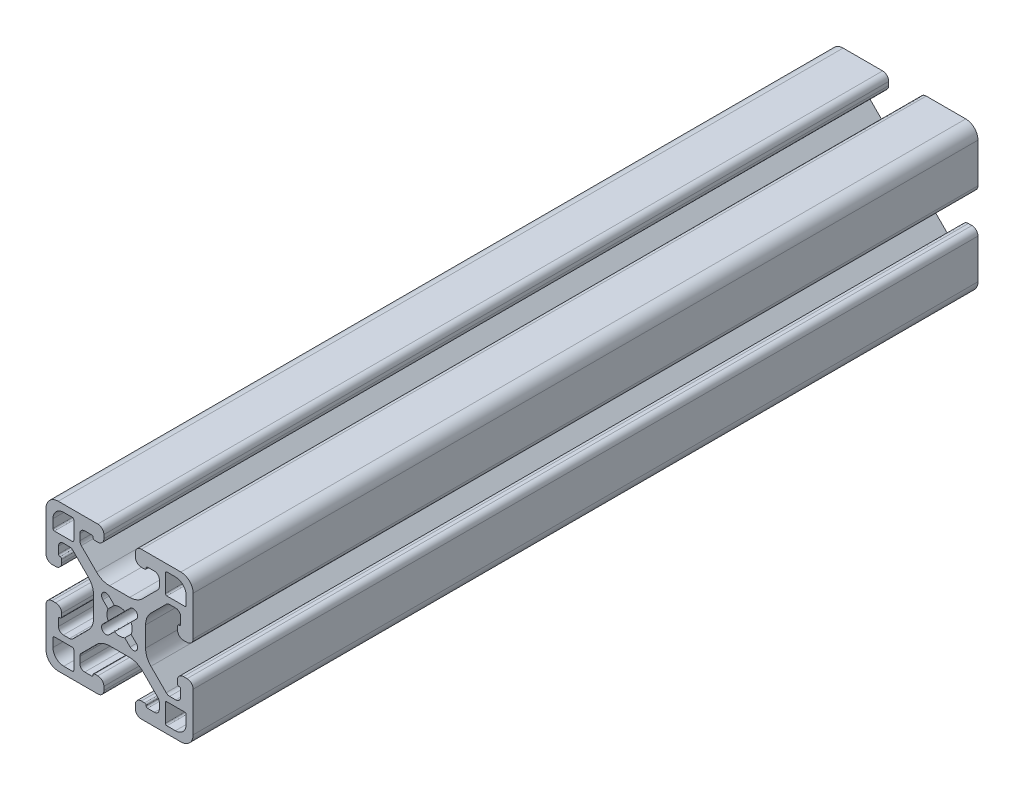
SolidWorks part; units mm, degrees
ref_plane "Front Plane" through (0, 0, 0) normal (0, 0, 1) x (1, 0, 0)
ref_plane "Top Plane" through (0, 0, 0) normal (0, 1, 0) x (1, 0, 0)
ref_plane "Right Plane" through (0, 0, 0) normal (1, 0, 0) x (0, 0, -1)
sketch "Sketch1" plane through (0, 0, 0) normal (0, 0, 1) x (1, 0, 0)
  line L0 (-66.7042, -2.4885) -> (-65.3338, -1.1181)
  line L1 (-65.3338, 1.5948) -> (-66.7042, 2.9652)
  line L2 (-65.0878, 4.5817) -> (-63.7174, 3.2113)
  line L3 (-61.0045, 3.2113) -> (-59.7212, 4.484)
  line L4 (-58.1153, 2.8781) -> (-59.3881, 1.5948)
  line L5 (-59.3881, -1.1181) -> (-58.0176, -2.4885)
  line L6 (-59.6341, -4.1049) -> (-61.0045, -2.7345)
  line L7 (-63.7174, -2.7345) -> (-65.0878, -4.1049)
  line L8 (-79.6075, 12.4812) -> (-79.6075, 14.691)
  line L9 (-76.8135, 17.485) -> (-74.6037, 17.485)
  line L10 (-74.2227, 17.104) -> (-74.2227, 12.4812)
  line L11 (-74.6037, 12.1002) -> (-79.2265, 12.1002)
  line L12 (-74.6037, -17.0082) -> (-76.8135, -17.0082)
  line L13 (-79.6075, -14.2142) -> (-79.6075, -12.0044)
  line L14 (-79.2265, -11.6234) -> (-74.6037, -11.6234)
  line L15 (-74.2227, -12.0044) -> (-74.2227, -16.6272)
  line L16 (-45.1143, -12.0044) -> (-45.1143, -14.2142)
  line L17 (-47.9083, -17.0082) -> (-50.1181, -17.0082)
  line L18 (-50.4991, -16.6272) -> (-50.4991, -12.0044)
  line L19 (-50.1181, -11.6234) -> (-45.4953, -11.6234)
  line L20 (-50.1181, 17.485) -> (-47.9083, 17.485)
  line L21 (-45.1143, 14.691) -> (-45.1143, 12.4812)
  line L22 (-45.4953, 12.1002) -> (-50.1181, 12.1002)
  line L23 (-50.4991, 12.4812) -> (-50.4991, 17.104)
  line L24 (-46.5368, -7.0006) -> (-46.5368, -8.7746)
  line L25 (-47.8067, -10.0486) -> (-49.3926, -10.0486)
  line L26 (-50.2907, -9.6767) -> (-54.2388, -5.7286)
  line L27 (-55.6299, -2.3699) -> (-55.6299, 2.8467)
  line L28 (-54.2388, 6.2053) -> (-50.2907, 10.1534)
  line L29 (-49.3926, 10.5254) -> (-47.8067, 10.5254)
  line L30 (-46.5368, 9.2513) -> (-46.5368, 7.4774)
  line L31 (-46.9178, 7.0964) -> (-46.994, 7.0964)
  line L32 (-47.375, 6.7154) -> (-47.3749, 5.8772)
  line L33 (-45.8001, 4.3024) -> (-44.8857, 4.3024)
  line L34 (-43.3109, 5.8772) -> (-43.3109, 16.1134)
  line L35 (-46.4859, 19.2884) -> (-56.7221, 19.2884)
  line L36 (-58.2969, 17.7136) -> (-58.2969, 16.7992)
  line L37 (-56.7222, 15.2244) -> (-55.884, 15.2244)
  line L38 (-55.503, 15.6054) -> (-55.503, 15.6816)
  line L39 (-55.122, 16.0626) -> (-53.348, 16.0626)
  line L40 (-52.0739, 14.7926) -> (-52.0739, 13.2067)
  line L41 (-52.4459, 12.3087) -> (-56.394, 8.3606)
  line L42 (-59.7526, 6.9694) -> (-64.9693, 6.9694)
  line L43 (-68.3279, 8.3606) -> (-72.276, 12.3087)
  line L44 (-72.6479, 13.2067) -> (-72.6479, 14.7926)
  line L45 (-71.3739, 16.0626) -> (-69.5999, 16.0626)
  line L46 (-69.2189, 15.6816) -> (-69.2189, 15.6054)
  line L47 (-68.8379, 15.2244) -> (-67.9997, 15.2244)
  line L48 (-66.4249, 16.7992) -> (-66.4249, 17.7136)
  line L49 (-67.9997, 19.2884) -> (-78.2359, 19.2884)
  line L50 (-81.4109, 16.1134) -> (-81.4109, 5.8772)
  line L51 (-79.8361, 4.3024) -> (-78.9217, 4.3024)
  line L52 (-77.3469, 5.8772) -> (-77.3469, 6.7154)
  line L53 (-77.7279, 7.0964) -> (-77.8041, 7.0964)
  line L54 (-78.1851, 7.4774) -> (-78.1851, 9.2513)
  line L55 (-76.9151, 10.5254) -> (-75.3293, 10.5254)
  line L56 (-74.4312, 10.1534) -> (-70.4831, 6.2053)
  line L57 (-69.0919, 2.8467) -> (-69.0919, -2.3699)
  line L58 (-70.4831, -5.7286) -> (-74.4312, -9.6767)
  line L59 (-75.3293, -10.0486) -> (-76.9151, -10.0486)
  line L60 (-78.1851, -8.7746) -> (-78.1851, -7.0006)
  line L61 (-77.8041, -6.6196) -> (-77.7279, -6.6196)
  line L62 (-77.3469, -6.2386) -> (-77.3469, -5.4004)
  line L63 (-78.9217, -3.8256) -> (-79.8361, -3.8256)
  line L64 (-81.4109, -5.4004) -> (-81.4109, -15.6366)
  line L65 (-78.2359, -18.8116) -> (-67.9997, -18.8116)
  line L66 (-66.4249, -17.2368) -> (-66.4249, -16.3224)
  line L67 (-67.9997, -14.7476) -> (-68.8379, -14.7476)
  line L68 (-69.2189, -15.1286) -> (-69.2189, -15.2048)
  line L69 (-69.5999, -15.5858) -> (-71.3739, -15.5858)
  line L70 (-72.6479, -14.3158) -> (-72.6479, -12.7299)
  line L71 (-72.276, -11.8319) -> (-68.3279, -7.8838)
  line L72 (-64.9693, -6.4926) -> (-59.7526, -6.4926)
  line L73 (-56.394, -7.8838) -> (-52.4459, -11.8319)
  line L74 (-52.0739, -12.7299) -> (-52.0739, -14.3158)
  line L75 (-53.348, -15.5858) -> (-55.122, -15.5858)
  line L76 (-55.503, -15.2048) -> (-55.503, -15.1286)
  line L77 (-55.884, -14.7476) -> (-56.7222, -14.7476)
  line L78 (-58.2969, -16.3224) -> (-58.2969, -17.2368)
  line L79 (-56.7221, -18.8116) -> (-46.4859, -18.8116)
  line L80 (-43.3109, -15.6366) -> (-43.3109, -5.4004)
  line L81 (-44.8857, -3.8256) -> (-45.8001, -3.8256)
  line L82 (-47.3749, -5.4004) -> (-47.375, -6.2386)
  line L83 (-46.994, -6.6196) -> (-46.9178, -6.6196)
  arc A0 (-66.7042, -2.4885) -> (-65.0878, -4.1049) centre (-65.896, -3.2967) ccw
  arc A1 (-65.3338, 1.5948) -> (-65.3338, -1.1181) centre (-62.3609, 0.2384) ccw
  arc A2 (-65.0878, 4.5817) -> (-66.7042, 2.9652) centre (-65.896, 3.7734) ccw
  arc A3 (-61.0045, 3.2113) -> (-63.7174, 3.2113) centre (-62.3609, 0.2384) ccw
  arc A4 (-58.1153, 2.8781) -> (-59.7212, 4.484) centre (-58.8259, 3.7734) ccw
  arc A5 (-59.3881, -1.1181) -> (-59.3881, 1.5948) centre (-62.3609, 0.2384) ccw
  arc A6 (-59.6341, -4.1049) -> (-58.0176, -2.4885) centre (-58.8259, -3.2967) ccw
  arc A7 (-63.7174, -2.7345) -> (-61.0045, -2.7345) centre (-62.3609, 0.2384) ccw
  arc A8 (-79.6075, 12.4812) -> (-79.2265, 12.1002) centre (-79.2265, 12.4812) ccw
  arc A9 (-76.8135, 17.485) -> (-79.6075, 14.691) centre (-76.8135, 14.691) ccw
  arc A10 (-74.2227, 17.104) -> (-74.6037, 17.485) centre (-74.6037, 17.104) ccw
  arc A11 (-74.6037, 12.1002) -> (-74.2227, 12.4812) centre (-74.6037, 12.4812) ccw
  arc A12 (-74.6037, -17.0082) -> (-74.2227, -16.6272) centre (-74.6037, -16.6272) ccw
  arc A13 (-79.6075, -14.2142) -> (-76.8135, -17.0082) centre (-76.8135, -14.2142) ccw
  arc A14 (-79.2265, -11.6234) -> (-79.6075, -12.0044) centre (-79.2265, -12.0044) ccw
  arc A15 (-74.2227, -12.0044) -> (-74.6037, -11.6234) centre (-74.6037, -12.0044) ccw
  arc A16 (-45.1143, -12.0044) -> (-45.4953, -11.6234) centre (-45.4953, -12.0044) ccw
  arc A17 (-47.9083, -17.0082) -> (-45.1143, -14.2142) centre (-47.9083, -14.2142) ccw
  arc A18 (-50.4991, -16.6272) -> (-50.1181, -17.0082) centre (-50.1181, -16.6272) ccw
  arc A19 (-50.1181, -11.6234) -> (-50.4991, -12.0044) centre (-50.1181, -12.0044) ccw
  arc A20 (-50.1181, 17.485) -> (-50.4991, 17.104) centre (-50.1181, 17.104) ccw
  arc A21 (-45.1143, 14.691) -> (-47.9083, 17.485) centre (-47.9083, 14.691) ccw
  arc A22 (-45.4953, 12.1002) -> (-45.1143, 12.4812) centre (-45.4953, 12.4812) ccw
  arc A23 (-50.4991, 12.4812) -> (-50.1181, 12.1002) centre (-50.1181, 12.4812) ccw
  arc A24 (-47.8067, -10.0486) -> (-46.5368, -8.7746) centre (-47.8067, -8.7786) ccw
  arc A25 (-50.2907, -9.6767) -> (-49.3926, -10.0486) centre (-49.3926, -8.7786) ccw
  arc A26 (-55.6299, -2.3699) -> (-54.2388, -5.7286) centre (-50.8801, -2.3699) ccw
  arc A27 (-54.2388, 6.2053) -> (-55.6299, 2.8467) centre (-50.8801, 2.8467) ccw
  arc A28 (-49.3926, 10.5254) -> (-50.2907, 10.1534) centre (-49.3926, 9.2554) ccw
  arc A29 (-46.5368, 9.2513) -> (-47.8067, 10.5254) centre (-47.8067, 9.2554) ccw
  arc A30 (-46.9178, 7.0964) -> (-46.5368, 7.4774) centre (-46.9178, 7.4774) ccw
  arc A31 (-46.994, 7.0964) -> (-47.375, 6.7154) centre (-46.994, 6.7154) ccw
  arc A32 (-47.3749, 5.8772) -> (-45.8001, 4.3024) centre (-45.8001, 5.8772) ccw
  arc A33 (-44.8857, 4.3024) -> (-43.3109, 5.8772) centre (-44.8857, 5.8772) ccw
  arc A34 (-43.3109, 16.1134) -> (-46.4859, 19.2884) centre (-46.4859, 16.1134) ccw
  arc A35 (-56.7221, 19.2884) -> (-58.2969, 17.7136) centre (-56.7221, 17.7136) ccw
  arc A36 (-58.2969, 16.7992) -> (-56.7222, 15.2244) centre (-56.7221, 16.7992) ccw
  arc A37 (-55.884, 15.2244) -> (-55.503, 15.6054) centre (-55.884, 15.6054) ccw
  arc A38 (-55.122, 16.0626) -> (-55.503, 15.6816) centre (-55.122, 15.6816) ccw
  arc A39 (-52.0739, 14.7926) -> (-53.348, 16.0626) centre (-53.3439, 14.7926) ccw
  arc A40 (-52.4459, 12.3087) -> (-52.0739, 13.2067) centre (-53.3439, 13.2067) ccw
  arc A41 (-59.7526, 6.9694) -> (-56.394, 8.3606) centre (-59.7526, 11.7192) ccw
  arc A42 (-68.3279, 8.3606) -> (-64.9693, 6.9694) centre (-64.9693, 11.7192) ccw
  arc A43 (-72.6479, 13.2067) -> (-72.276, 12.3087) centre (-71.3779, 13.2067) ccw
  arc A44 (-71.3739, 16.0626) -> (-72.6479, 14.7926) centre (-71.3779, 14.7926) ccw
  arc A45 (-69.2189, 15.6816) -> (-69.5999, 16.0626) centre (-69.5999, 15.6816) ccw
  arc A46 (-69.2189, 15.6054) -> (-68.8379, 15.2244) centre (-68.8379, 15.6054) ccw
  arc A47 (-67.9997, 15.2244) -> (-66.4249, 16.7992) centre (-67.9997, 16.7992) ccw
  arc A48 (-66.4249, 17.7136) -> (-67.9997, 19.2884) centre (-67.9997, 17.7136) ccw
  arc A49 (-78.2359, 19.2884) -> (-81.4109, 16.1134) centre (-78.2359, 16.1134) ccw
  arc A50 (-81.4109, 5.8772) -> (-79.8361, 4.3024) centre (-79.8361, 5.8772) ccw
  arc A51 (-78.9217, 4.3024) -> (-77.3469, 5.8772) centre (-78.9217, 5.8772) ccw
  arc A52 (-77.3469, 6.7154) -> (-77.7279, 7.0964) centre (-77.7279, 6.7154) ccw
  arc A53 (-78.1851, 7.4774) -> (-77.8041, 7.0964) centre (-77.8041, 7.4774) ccw
  arc A54 (-76.9151, 10.5254) -> (-78.1851, 9.2513) centre (-76.9151, 9.2554) ccw
  arc A55 (-74.4312, 10.1534) -> (-75.3293, 10.5254) centre (-75.3293, 9.2554) ccw
  arc A56 (-69.0919, 2.8467) -> (-70.4831, 6.2053) centre (-73.8417, 2.8467) ccw
  arc A57 (-70.4831, -5.7286) -> (-69.0919, -2.3699) centre (-73.8417, -2.3699) ccw
  arc A58 (-75.3293, -10.0486) -> (-74.4312, -9.6767) centre (-75.3293, -8.7786) ccw
  arc A59 (-78.1851, -8.7746) -> (-76.9151, -10.0486) centre (-76.9151, -8.7786) ccw
  arc A60 (-77.8041, -6.6196) -> (-78.1851, -7.0006) centre (-77.8041, -7.0006) ccw
  arc A61 (-77.7279, -6.6196) -> (-77.3469, -6.2386) centre (-77.7279, -6.2386) ccw
  arc A62 (-77.3469, -5.4004) -> (-78.9217, -3.8256) centre (-78.9217, -5.4004) ccw
  arc A63 (-79.8361, -3.8256) -> (-81.4109, -5.4004) centre (-79.8361, -5.4004) ccw
  arc A64 (-81.4109, -15.6366) -> (-78.2359, -18.8116) centre (-78.2359, -15.6366) ccw
  arc A65 (-67.9997, -18.8116) -> (-66.4249, -17.2368) centre (-67.9997, -17.2368) ccw
  arc A66 (-66.4249, -16.3224) -> (-67.9997, -14.7476) centre (-67.9997, -16.3224) ccw
  arc A67 (-68.8379, -14.7476) -> (-69.2189, -15.1286) centre (-68.8379, -15.1286) ccw
  arc A68 (-69.5999, -15.5858) -> (-69.2189, -15.2048) centre (-69.5999, -15.2048) ccw
  arc A69 (-72.6479, -14.3158) -> (-71.3739, -15.5858) centre (-71.3779, -14.3158) ccw
  arc A70 (-72.276, -11.8319) -> (-72.6479, -12.7299) centre (-71.3779, -12.7299) ccw
  arc A71 (-64.9693, -6.4926) -> (-68.3279, -7.8838) centre (-64.9693, -11.2424) ccw
  arc A72 (-56.394, -7.8838) -> (-59.7526, -6.4926) centre (-59.7526, -11.2424) ccw
  arc A73 (-52.0739, -12.7299) -> (-52.4459, -11.8319) centre (-53.3439, -12.7299) ccw
  arc A74 (-53.348, -15.5858) -> (-52.0739, -14.3158) centre (-53.3439, -14.3158) ccw
  arc A75 (-55.503, -15.2048) -> (-55.122, -15.5858) centre (-55.122, -15.2048) ccw
  arc A76 (-55.503, -15.1286) -> (-55.884, -14.7476) centre (-55.884, -15.1286) ccw
  arc A77 (-56.7222, -14.7476) -> (-58.2969, -16.3224) centre (-56.7221, -16.3224) ccw
  arc A78 (-58.2969, -17.2368) -> (-56.7221, -18.8116) centre (-56.7221, -17.2368) ccw
  arc A79 (-46.4859, -18.8116) -> (-43.3109, -15.6366) centre (-46.4859, -15.6366) ccw
  arc A80 (-43.3109, -5.4004) -> (-44.8857, -3.8256) centre (-44.8857, -5.4004) ccw
  arc A81 (-45.8001, -3.8256) -> (-47.3749, -5.4004) centre (-45.8001, -5.4004) ccw
  arc A82 (-47.375, -6.2386) -> (-46.994, -6.6196) centre (-46.994, -6.2386) ccw
  arc A83 (-46.5368, -7.0006) -> (-46.9178, -6.6196) centre (-46.9178, -7.0006) ccw
extrude "Extrude1" add sketch "Sketch1" against normal blind 203.2
